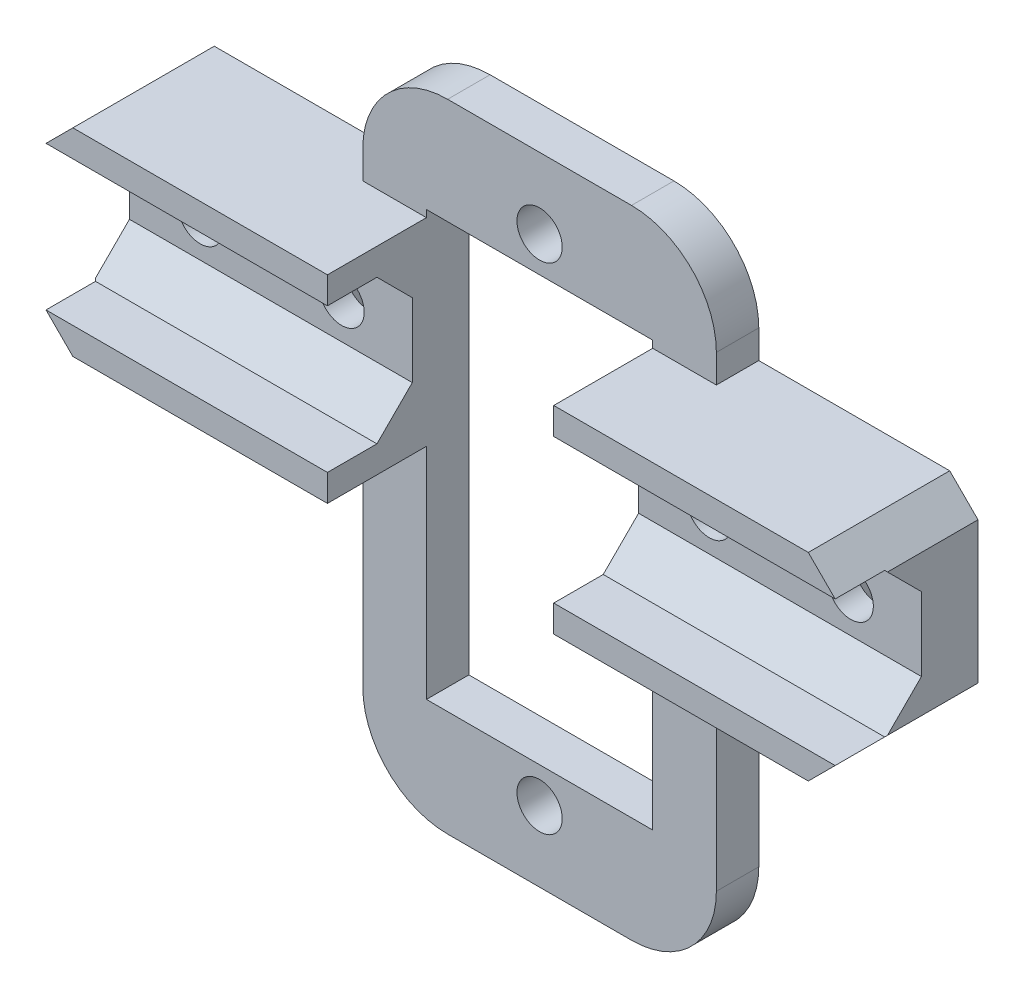
SolidWorks part; units mm, degrees
ref_plane "Plan de face" through (0, 0, 0) normal (0, 0, 1) x (1, 0, 0)
ref_plane "Plan de dessus" through (0, 0, 0) normal (0, 1, 0) x (1, 0, 0)
ref_plane "Plan de droite" through (0, 0, 0) normal (1, 0, 0) x (0, 0, -1)
sketch "Esquisse1" plane through (0, 0, 0) normal (0, 0, 1) x (1, 0, 0)
  line L0 (-12.5, 14.5) -> (-12.5, 22.5)
  line L1 (-12.5, -22.5) -> (12.5, -22.5)
  line L2 (-12.5, -22.5) -> (-12.5, 0.5)
  line L3 (-12.5, 22.5) -> (12.5, 22.5)
  line L4 (12.5, -22.5) -> (12.5, 0.5)
  line L5 (-12.5, -22.5) -> (12.5, 22.5) construction
  line L6 (-12.5, 22.5) -> (12.5, -22.5) construction
  line L7 (-12.5, 14.5) -> (-28, 14.5)
  line L8 (12.5, 14.5) -> (12.5, 22.5)
  line L9 (-12.5, 0.5) -> (-28, 0.5)
  line L10 (-28, 14.5) -> (-28, 0.5)
  line L11 (12.5, 14.5) -> (28, 14.5)
  line L13 (12.5, 0.5) -> (28, 0.5)
  line L14 (28, 14.5) -> (28, 0.5)
  line L15 (-8, -15) -> (8, -15)
  line L16 (-8, -15) -> (-8, 15)
  line L17 (-8, 15) -> (8, 15)
  line L18 (8, -15) -> (8, 15)
  line L19 (-8, -15) -> (8, 15) construction
  line L20 (-8, 15) -> (8, -15) construction
  circle A0 centre (0, 17.5) radius 1.6
  circle A1 centre (0, -17.5) radius 1.6
  point P0 (0, 0)
  point P14 (0, 0)
  dimension "D11" = 3.2
  dimension "D13" = 3.2
  dimension "D1" = 25
  dimension "D2" = 45
  dimension "D3" = 28
  dimension "D4" = 14
  dimension "D5" = 14.5
  dimension "D7" = 14
  dimension "D8" = 28
  dimension "D9" = 16
  dimension "D10" = 30
  dimension "D12" = 2.5
  dimension "D14" = 2.5
extrude "Boss.-Extru.1" add sketch "Esquisse1" along normal blind 3
sketch "Esquisse2" plane through (0, 0, 3) normal (0, 0, 1) x (1, 0, 0)
  line L0 (-8, 15) -> (-8, -15) construction
  line L1 (-28, 14.5) -> (-8, 14.5)
  line L2 (-28, 14.5) -> (-28, 0.5)
  line L3 (-28, 0.5) -> (-8, 0.5)
  line L4 (-8, 14.5) -> (-8, 0.5)
  line L5 (8, -15) -> (8, 15) construction
  line L6 (28, 14.5) -> (8, 14.5)
  line L7 (28, 14.5) -> (28, 0.5)
  line L8 (28, 0.5) -> (8, 0.5)
  line L9 (8, 14.5) -> (8, 0.5)
  dimension "D1" = 14
  dimension "D2" = 14
extrude "Boss.-Extru.2" add sketch "Esquisse2" along normal blind 7
sketch "Esquisse3" plane through (-28, 0, 0) normal (-1, 0, 0) x (0, 0, 1)
  line L0 (0, 14.5) -> (0, 0.5) construction
  line L1 (13.6719, 12.6) -> (4, 12.6)
  line L2 (13.6719, 12.6) -> (13.6719, 2.4)
  line L3 (13.6719, 2.4) -> (4, 2.4)
  line L4 (4, 12.6) -> (4, 2.4)
  line L5 (10, 14.5) -> (10, 0.5) construction
  point P4 (0, 7.5)
  dimension "D1" = 5.1
  dimension "D2" = 10.2
  dimension "D3" = 6
extrude "Enlèv. mat.-Extru.1" cut sketch "Esquisse3" against normal through all
chamfer "Chanfrein1" distance 2 angle 45 4 edges at (28, 0.5, 5) (28, 14.5, 5) (-28, 0.5, 5) (-28, 14.5, 5)
chamfer "Chanfrein2" distance 2.5 angle 45 4 edges at (-17.95, 12.6, 4) (-17.95, 2.4, 4) (17.95, 12.6, 4) (17.95, 2.4, 4)
sketch "Esquisse4" plane through (0, 0, 0) normal (0, 0, -1) x (-1, 0, 0)
  line L0 (41.0277, 7.5) -> (-64.7712, 7.5) construction
  line L1 (-28, 2.5) -> (-28, 12.5) construction
  line L2 (26, 0.5) -> (12.5, 0.5) construction
  line L3 (28, 12.5) -> (28, 2.5) construction
  circle A0 centre (23, 7.5) radius 1.6
  circle A1 centre (13, 7.5) radius 1.6
  circle A2 centre (-13, 7.5) radius 1.6
  circle A3 centre (-23, 7.5) radius 1.6
  dimension "D1" = 3.2
  dimension "D2" = 3.2
  dimension "D3" = 3.2
  dimension "D4" = 3.2
  dimension "D5" = 5
  dimension "D6" = 10
  dimension "D7" = 5
  dimension "D8" = 10
  dimension "D9" = 7
extrude "Enlèv. mat.-Extru.2" cut sketch "Esquisse4" against normal blind 7
fillet "Congé1" radius 6 4 edges at (12.5, -22.5, 1.5) (-12.5, -22.5, 1.5) (-12.5, 22.5, 1.5) (12.5, 22.5, 1.5)
chamfer "Chanfrein3" distance 2.1 angle 45 4 edges at (-24.6, 7.5, 0) (-14.6, 7.5, 0) (11.4, 7.5, 0) (21.4, 7.5, 0)
